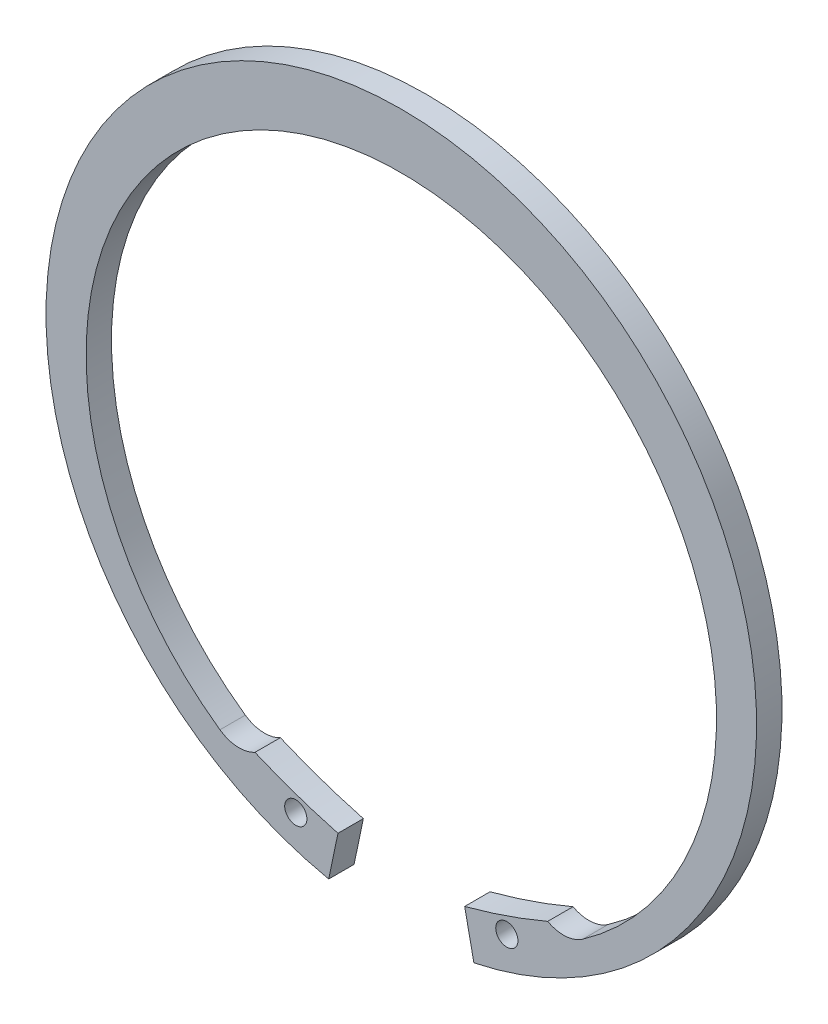
SolidWorks part; units mm, degrees
ref_plane "Front Plane" through (0, 0, 0) normal (0, 0, 1) x (1, 0, 0)
ref_plane "Top Plane" through (0, 0, 0) normal (0, 1, 0) x (1, 0, 0)
ref_plane "Right Plane" through (0, 0, 0) normal (1, 0, 0) x (0, 0, -1)
sketch "Sketch1" plane through (0, 0, 0) normal (0, 0, 1) x (1, 0, 0)
  line L0 (0, 56) -> (0, 47.3) construction
  line L1 (-30.9944, -46.6406) -> (-28.5868, -43.0177) construction
  line L2 (0, 0) -> (0, -56) construction
  line L3 (-9.5, -45.5192) -> (-11.4409, -54.8189) construction
  line L4 (-9.5, -45.5192) -> (-13, -45.5192) construction
  circle A0 centre (0, 0) radius 54.5 construction
  circle A1 centre (0, 0) radius 56 construction
  circle A2 centre (0, 0) radius 52.5 construction
  dimension "Ring OD" = 112
  dimension "For ID" = 105
  dimension "Maximum Section" = 8.7
  dimension "Maximum Lug Height" = 9.5
  dimension "Hole Diameter" = 3.5
  dimension "D2" = 4.35
  dimension "Gap Width" = 19
  dimension "D1" = 19.25
sketch "Sketch2" plane through (0, 0, 0) normal (1, 0, 0) x (0, 0, -1)
  line L0 (-2.075, 56) -> (2.075, 56) construction
  line L1 (-2, -56) -> (2, -56) construction
  point P3 (0, 56)
  point P7 (0, -56)
  point P8 (-2, -56)
  point P10 (2, -56)
  point P11 (-2.075, 56)
  point P12 (2.075, 56)
  dimension "For Groove Width" = 4.15
  dimension "Ring Thickness" = 4
sketch "Sketch3" plane through (0, 0, 0) normal (0, 0, 1) x (1, 0, 0)
  line L0 (-11.4409, -54.8189) -> (-9.9852, -47.8441)
  line L1 (-9.9852, -47.8441) -> (-23.0692, -43.3421)
  line L2 (0, 0) -> (-15.7769, -45.8513) construction
  line L3 (-28.5868, -43.0177) -> (28.5868, -43.0177) construction
  line L4 (0, 0) -> (0, -56) construction
  line L7 (-16.631, -48.3334) -> (-15.7769, -45.8513) construction
  line L8 (0, 56) -> (0, 47.3) construction
  line L9 (9.9852, -47.8441) -> (23.0692, -43.3421)
  line L10 (11.4409, -54.8189) -> (9.9852, -47.8441)
  line L12 (-9.5, -45.5192) -> (-11.4409, -54.8189) construction
  arc A0 (-11.4409, -54.8189) -> (11.4409, -54.8189) centre (0, 0) cw
  circle A1 centre (0, 0) radius 56 construction
  arc A2 (-28.5868, -43.0177) -> (28.5868, -43.0177) centre (0, -2.3829) cw
  arc A3 (-28.5868, -43.0177) -> (-23.0692, -43.3421) centre (-25.566, -38.7238) ccw
  circle A4 centre (-16.631, -48.3334) radius 1.75
  circle A5 centre (0, 0) radius 51.65 construction
  arc A6 (28.5868, -43.0177) -> (23.0692, -43.3421) centre (25.566, -38.7238) cw
  circle A7 centre (16.631, -48.3334) radius 1.75
  point P3 (0, -43.0177)
  dimension "D1" = 3.5
  dimension "D5" = 5.25
  dimension "D2" = 6.125
  dimension "D3" = 7.125
  dimension "D4" = 2.625
extrude "Boss-Extrude1" add sketch "Sketch3" against normal up to vertex (2 mm away) and the other way up to vertex (2 mm away) up to point (0, -56, -2) other way up to point (0, -56, 2)
sketch "Sketch5" plane through (0, 0, 0) normal (0, 0, 1) x (1, 0, 0)
  line L1 (-23.0692, -43.3421) -> (0, 0)
  line L2 (0, 0) -> (-9.9852, -47.8441)
  line L3 (-9.9852, -47.8441) -> (-23.0692, -43.3421) construction
  arc A0 (-23.0692, -43.3421) -> (-9.9852, -47.8441) centre (14.5794, 44.8097) ccw
  arc A3 (-28.5868, -43.0177) -> (-23.0692, -43.3421) centre (-25.566, -38.7238) ccw construction
  point P3 (-16.6086, -45.8295)
  dimension "D1" = 0.25
extrude "Cut-Extrude2" cut sketch "Sketch5" against normal through all both and the other way through all
mirror "Mirror1" about plane through (0, 0, 0) normal (1, 0, 0) of "Cut-Extrude2"
equation "\"D1@Sketch3\"=\"Hole Diameter@Sketch1\""
equation "\"D2@Sketch3\"=\"Hole Diameter@Sketch1\"*1.75"
equation "\"D2@Sketch1\"=\"Maximum Section@Sketch1\"*.5"
equation "\"Gap Width@Sketch1\" = \"Maximum Lug Height@Sketch1\" * 2"
equation "\"D3@Sketch3\" = \"Maximum Lug Height@Sketch1\" * .75"
equation "\"D4@Sketch3\"=\"Hole Diameter@Sketch1\"*.75"
equation "\"D1@Sketch1\"=\"Hole Diameter@Sketch1\"*5.5"
equation "\"D5@Sketch3\"=\"Hole Diameter@Sketch1\"*1.5"
